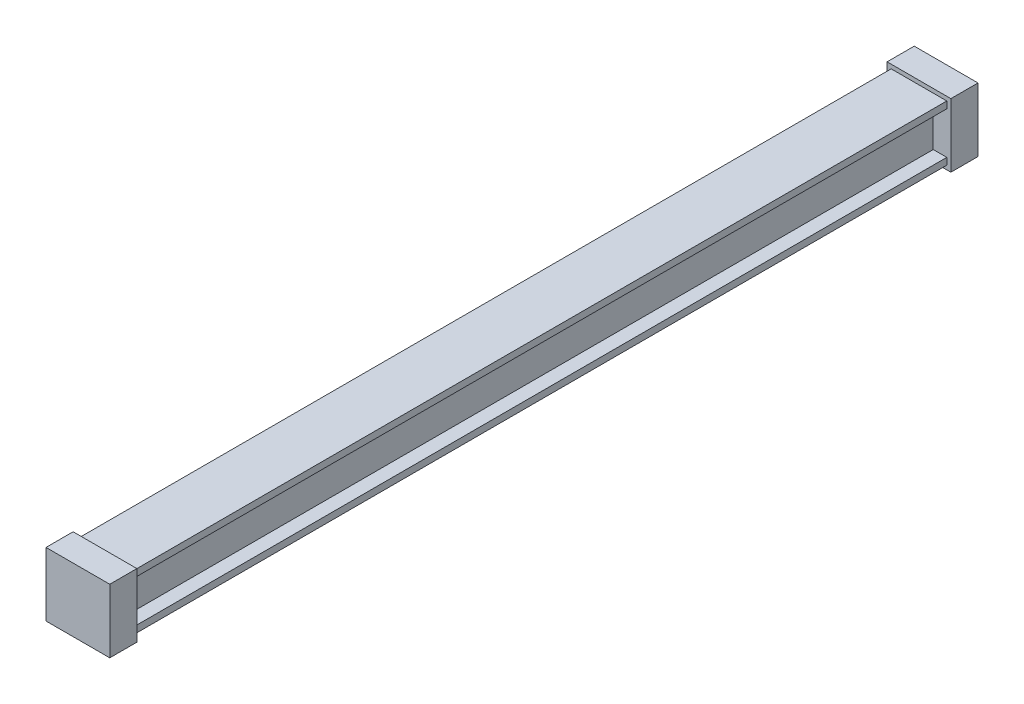
SolidWorks part; units mm, degrees
ref_plane "Front Plane" through (0, 0, 0) normal (0, 0, 1) x (1, 0, 0)
ref_plane "Top Plane" through (0, 0, 0) normal (0, 1, 0) x (1, 0, 0)
ref_plane "Right Plane" through (0, 0, 0) normal (1, 0, 0) x (0, 0, -1)
sketch "Sketch1" plane through (0, 0, 0) normal (0, 0, 1) x (1, 0, 0)
  line L1 (-20.5, -20.5) -> (20.5, -20.5)
  line L2 (-20.5, -20.5) -> (-20.5, 20.5)
  line L3 (-20.5, 20.5) -> (20.5, 20.5)
  line L4 (20.5, -20.5) -> (20.5, 20.5)
  line L5 (-20.5, -20.5) -> (20.5, 20.5) construction
  line L6 (-20.5, 20.5) -> (20.5, -20.5) construction
  point P0 (0, 0)
  dimension "D1" = 41
  dimension "D2" = 41
extrude "Boss-Extrude1" add sketch "Sketch1" along normal blind 640
sketch "Sketch2" plane through (0, 0, 0) normal (0, 0, -1) x (-1, 0, 0)
  line L0 (-20.5, -20.5) -> (-20.5, 20.5) construction
  line L1 (23.5, -23.5) -> (-23.5, -23.5)
  line L2 (23.5, -23.5) -> (23.5, 23.5)
  line L3 (23.5, 23.5) -> (-23.5, 23.5)
  line L4 (-23.5, -23.5) -> (-23.5, 23.5)
  line L5 (23.5, -23.5) -> (-23.5, 23.5) construction
  line L6 (23.5, 23.5) -> (-23.5, -23.5) construction
  line L7 (20.5, -20.5) -> (-20.5, -20.5) construction
  point P0 (0, 0)
  dimension "D1" = 3
  dimension "D2" = 3
extrude "Boss-Extrude2" add sketch "Sketch2" against normal blind 20
ref_plane "Plane1" through (0, 0, 320) normal (0, 0, -1) x (-1, 0, 0)
mirror "Mirror1" about plane through (0, 0, 320) normal (0, 0, -1) of "Boss-Extrude2"
sketch "Sketch3" plane through (20.5, 0, 0) normal (1, 0, 0) x (0, 0, -1)
  line L0 (-620, -20.5) -> (-620, 20.5) construction
  line L1 (-620, -15.5) -> (-20, -15.5)
  line L2 (-620, -15.5) -> (-620, 15.5)
  line L3 (-620, 15.5) -> (-20, 15.5)
  line L4 (-20, -15.5) -> (-20, 15.5)
  line L5 (-20, 20.5) -> (-20, -20.5) construction
  line L6 (-620, 20.5) -> (-20, 20.5) construction
  point P4 (-620, 0)
  point P7 (-620, 0)
  dimension "D1" = 5
extrude "Cut-Extrude1" cut sketch "Sketch3" against normal blind 10
